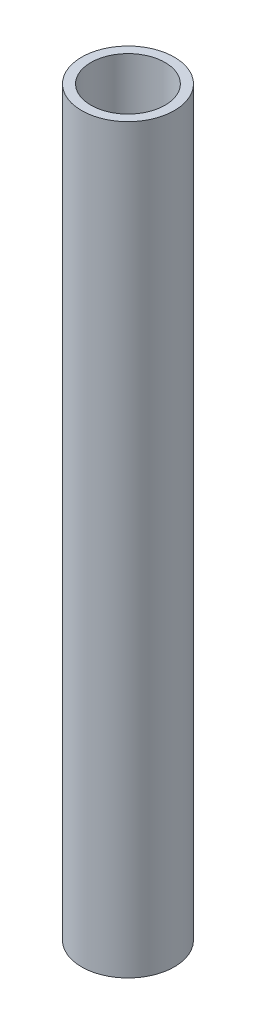
SolidWorks part; units mm, degrees
material "铝青铜"
ref_plane "前视基准面" through (0, 0, 0) normal (0, 0, 1) x (1, 0, 0)
ref_plane "上视基准面" through (0, 0, 0) normal (0, 1, 0) x (1, 0, 0)
ref_plane "右视基准面" through (0, 0, 0) normal (1, 0, 0) x (0, 0, -1)
sketch "草图1" plane through (0, 0, 0) normal (0, 1, 0) x (1, 0, 0)
  circle A0 centre (0, 0) radius 2
  circle A1 centre (0, 0) radius 2.5
extrude "凸台-拉伸1" add sketch "草图1" along normal blind 40
